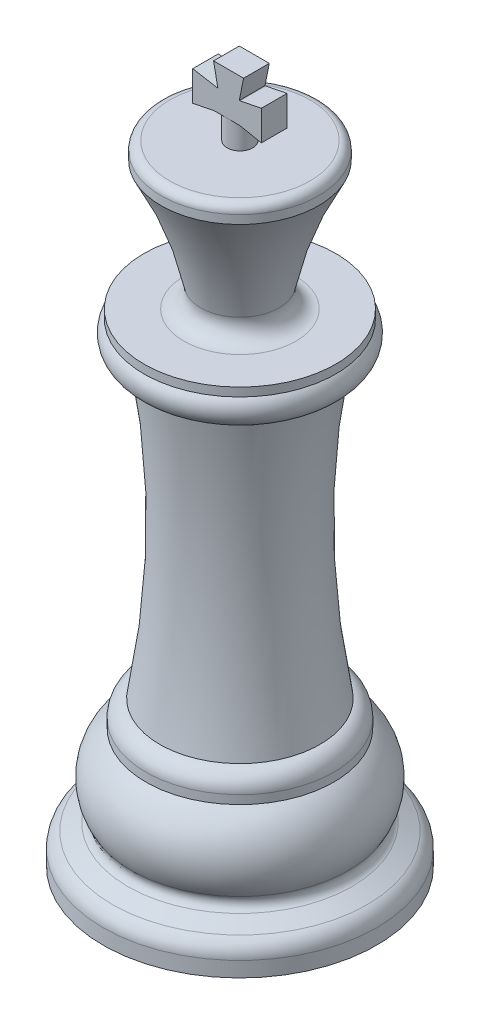
SolidWorks part; units mm, degrees
ref_plane "Front Plane" through (0, 0, 0) normal (0, 0, 1) x (1, 0, 0)
ref_plane "Top Plane" through (0, 0, 0) normal (0, 1, 0) x (1, 0, 0)
ref_plane "Right Plane" through (0, 0, 0) normal (1, 0, 0) x (0, 0, -1)
sketch "Sketch3" plane through (0, 0, 0) normal (0, 0, 1) x (1, 0, 0)
  line L1 (-0.6823, -7.57) -> (13.2771, -7.57)
  line L2 (11.3097, -2.57) -> (15.2771, -4.57)
  line L3 (15.2771, -4.57) -> (15.2771, -7.57)
  line L4 (15.2771, -7.57) -> (13.2771, -7.57)
  line L5 (10.2771, 6.4) -> (10.2771, 7.4)
  line L8 (10.5, 48.72) -> (10.5, 47.72)
  line L17 (-0.6823, 68.72) -> (-0.6823, -7.57)
  line L18 (10.5, 63.72) -> (8.5, 63.72)
  line L19 (8.5, 63.72) -> (8.5, 64.72)
  line L20 (7.5, 65.72) -> (0.8177, 65.72)
  line L22 (0.8177, 65.72) -> (0.8177, 68.72)
  line L23 (0.8177, 68.72) -> (-0.6823, 68.72)
  line L24 (10.5, 48.72) -> (3.5, 48.72)
  arc A0 (10.2771, 6.4) -> (11.3097, -2.57) centre (6.8692, 1.4633) cw
  arc A1 (8.6635, 9.4) -> (10.2771, 7.4) centre (8.2775, 7.4376) cw
  arc A2 (10.5, 47.72) -> (8.5, 44.4) centre (9.0765, 46.3151) cw
  arc A3 (8.6635, 9.4) -> (8.5, 44.4) centre (107.0375, 27.3599) cw
  arc A5 (8.5, 64.72) -> (7.5, 65.72) centre (7.5, 64.72) ccw
  arc A6 (3.5, 48.72) -> (8.5, 63.72) centre (45.7505, 42.9698) cw
  point P15 (0, 63)
  dimension "D9" = 2
  dimension "D10" = 2
  dimension "D11" = 5.9988
  dimension "D13" = 100
  dimension "D16" = 7
  dimension "D15" = 1
  dimension "D2" = 3
  dimension "D3" = 2
  dimension "D4" = 8.97
  dimension "D5" = 1
  dimension "D6" = 2
  dimension "D7" = 3.32
  dimension "D8" = 1
  dimension "D12" = 35
  dimension "D14" = 15
  dimension "D17" = 2
  dimension "D18" = 3
  dimension "D19" = 1.5
  dimension "D20" = 76.29
revolve "Revolve1" add sketch "Sketch3" angle 360 about L17
sketch3d "3DSketch1"
  point P0 (-0.7472, 65.9216, 1.4986)
ref_plane "Plane1" through (0, 0, 1.4986) normal (0, 0, 1) x (1, 0, 0)
sketch "Sketch4" plane through (0, 0, 1.4986) normal (0, 0, 1) x (1, 0, 0)
  line L12 (3.3177, 71.72) -> (0.8177, 71.22)
  line L14 (-4.6823, 71.72) -> (-1.8288, 71.22)
  line L15 (3.3177, 68.22) -> (0.8177, 68.72)
  line L19 (-4.6823, 68.22) -> (-4.6823, 71.72)
  line L21 (3.3177, 71.72) -> (3.3177, 68.22)
  line L24 (0.8177, 68.72) -> (-2.1823, 68.72)
  line L25 (-2.1823, 68.72) -> (-4.6823, 68.22)
  line L27 (1.2445, 73.72) -> (-2.2555, 73.72)
  line L36 (1.2445, 73.72) -> (0.7445, 71.22)
  line L37 (-2.2555, 73.72) -> (-1.7555, 71.22)
  line L38 (-1.7555, 71.22) -> (-1.8288, 71.22)
  line L39 (0.7445, 71.22) -> (0.8177, 71.22)
  dimension "D1" = 3.5
  dimension "D2" = 3.5
  dimension "D3" = 3.5
  dimension "D4" = 0.5
  dimension "D5" = 0.5
  dimension "D6" = 0.5
  dimension "D7" = 0.5
  dimension "D8" = 0
  dimension "D9" = 0.5
  dimension "D10" = 0.5
  dimension "D11" = 2.5
  dimension "D12" = 2.5
extrude "Boss-Extrude1" add sketch "Sketch4" against normal blind 3
fillet "Fillet1" radius 2 1 edges at (-16.6417, -4.57, 0)
fillet "Fillet2" radius 1 1 edges at (-12.6743, -2.57, 0)
fillet "Fillet3" radius 2 1 edges at (-4.8646, 48.72, 0)
